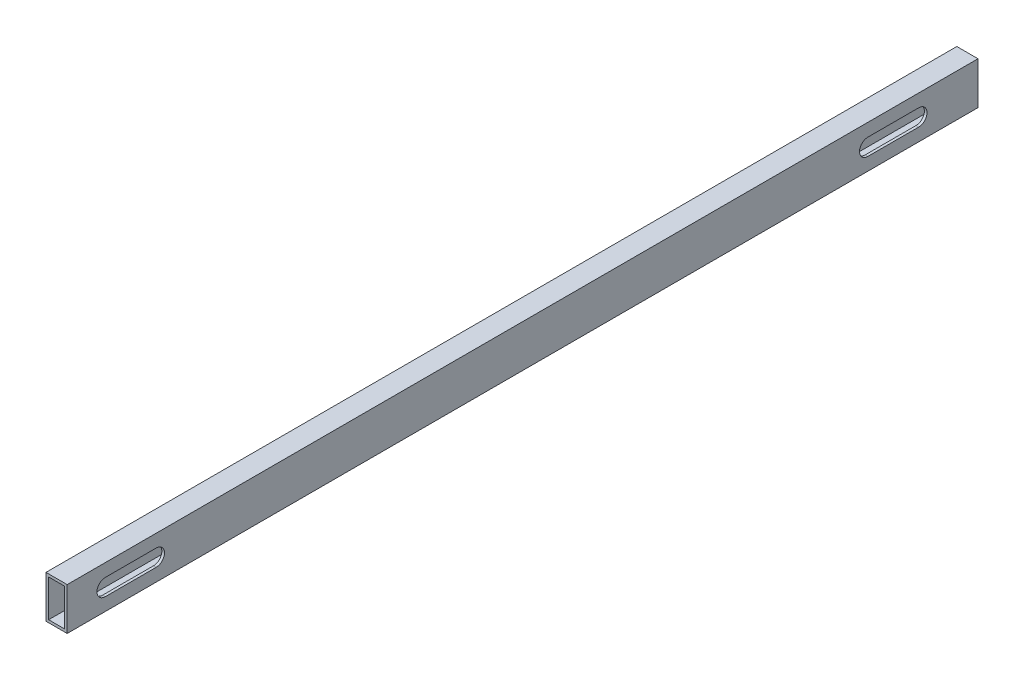
SolidWorks part; units mm, degrees
ref_plane "Front Plane" through (0, 0, 0) normal (0, 0, 1) x (1, 0, 0)
ref_plane "Top Plane" through (0, 0, 0) normal (0, 1, 0) x (1, 0, 0)
ref_plane "Right Plane" through (0, 0, 0) normal (1, 0, 0) x (0, 0, -1)
sketch "Sketch1" plane through (0, 0, 0) normal (0, 0, 1) x (1, 0, 0)
  line L1 (-6.35, -12.7) -> (6.35, -12.7)
  line L2 (-6.35, -12.7) -> (-6.35, 12.7)
  line L3 (-6.35, 12.7) -> (6.35, 12.7)
  line L4 (6.35, -12.7) -> (6.35, 12.7)
  line L6 (-6.35, 12.7) -> (6.35, -12.7) construction
  line L7 (-4.7625, -11.1125) -> (4.7625, -11.1125)
  line L8 (-4.7625, -11.1125) -> (-4.7625, 11.1125)
  line L9 (-4.7625, 11.1125) -> (4.7625, 11.1125)
  line L10 (4.7625, -11.1125) -> (4.7625, 11.1125)
  line L11 (-4.7625, -11.1125) -> (4.7625, 11.1125) construction
  line L12 (-4.7625, 11.1125) -> (4.7625, -11.1125) construction
  point P0 (0, 0)
  point P6 (0, 0)
  dimension "D1" = 25.4
  dimension "D2" = 1.5875
  dimension "D3" = 12.7
  dimension "D4" = 1.5875
  dimension "D5" = 1.5875
extrude "Boss-Extrude1" add sketch "Sketch1" along normal blind 546.1
sketch "Sketch2" plane through (6.35, 0, 0) normal (1, 0, 0) x (0, 0, -1)
  line L0 (-546.1, 0) -> (0, 0) construction
  line L1 (-546.1, -12.7) -> (-546.1, 12.7) construction
  line L2 (-508, 12.7) -> (-508, -12.7) construction
  line L3 (-44.45, 0) -> (-57.15, 0) construction
  line L4 (-44.45, -3.302) -> (-57.15, -3.302)
  line L5 (-44.45, 3.302) -> (-57.15, 3.302)
  line L6 (-546.1, 12.7) -> (0, 12.7) construction
  line L7 (-546.1, -12.7) -> (0, -12.7) construction
  line L8 (-50.8, 12.7) -> (-50.8, -12.7) construction
  circle A0 centre (-508, 0) radius 3.81
  arc A2 (-44.45, -3.302) -> (-44.45, 3.302) centre (-44.45, 0) ccw
  arc A3 (-57.15, 3.302) -> (-57.15, -3.302) centre (-57.15, 0) ccw
  circle A4 centre (-523.24, 0) radius 2.75
  circle A5 centre (-492.76, 0) radius 2.75
  point P9 (-50.8, 0)
  dimension "D1" = 7.62
  dimension "D2" = 3.302
  dimension "D6" = 5.5
  dimension "D3" = 38.1
  dimension "D4" = 12.7
  dimension "D5" = 457.2
  dimension "D7" = 30.48
extrude "Cut-Extrude1" cut sketch "Sketch2" against normal through all
sketch "Sketch3" plane through (0, 0, 546.1) normal (0, 0, 1) x (1, 0, 0)
  line L0 (-6.35, 12.7) -> (-6.35, -12.7) construction
  line L1 (-4.7625, 11.1125) -> (-6.35, 11.1125)
  line L2 (-4.7625, 11.1125) -> (-4.7625, -11.1125)
  line L3 (-4.7625, -11.1125) -> (-6.35, -11.1125)
  line L4 (-6.35, 11.1125) -> (-6.35, -11.1125)
  line L5 (-4.7625, -11.1125) -> (4.7625, -11.1125) construction
sketch "Sketch4" plane through (6.35, 0, 0) normal (-1, 0, 0) x (0, 0, 1)
  line L0 (35.56, 0) -> (66.04, 0) construction
  line L1 (35.56, 5) -> (66.04, 5)
  line L2 (35.56, -5) -> (66.04, -5)
  line L3 (492.76, 0) -> (523.24, 0) construction
  line L4 (492.76, 5) -> (523.24, 5)
  line L5 (492.76, -5) -> (523.24, -5)
  arc A0 (35.56, 5) -> (35.56, -5) centre (35.56, 0) ccw
  arc A1 (66.04, -5) -> (66.04, 5) centre (66.04, 0) ccw
  arc A2 (492.76, 5) -> (492.76, -5) centre (492.76, 0) ccw
  arc A3 (523.24, -5) -> (523.24, 5) centre (523.24, 0) ccw
  point P2 (50.8, 0)
  point P13 (508, 0)
  dimension "D1" = 5
extrude "Cut-Extrude3" cut sketch "Sketch4" along normal up to next
sketch "Sketch5" plane through (0, -12.7, 0) normal (0, -1, 0) x (1, 0, 0)
  line L0 (-6.35, 546.1) -> (6.35, 546.1) construction
  line L1 (0, 546.1) -> (0, 0) construction
  line L2 (-6.35, 273.05) -> (6.35, 273.05) construction
  line L3 (-6.35, 546.1) -> (-6.35, 0) construction
  line L4 (6.35, 546.1) -> (6.35, 0) construction
  circle A0 centre (0, 533.4) radius 2.75
  circle A1 centre (0, 12.7) radius 2.75
  dimension "D1" = 5.5
  dimension "D2" = 12.7
extrude "Cut-Extrude5" cut sketch "Sketch5" against normal up to next
